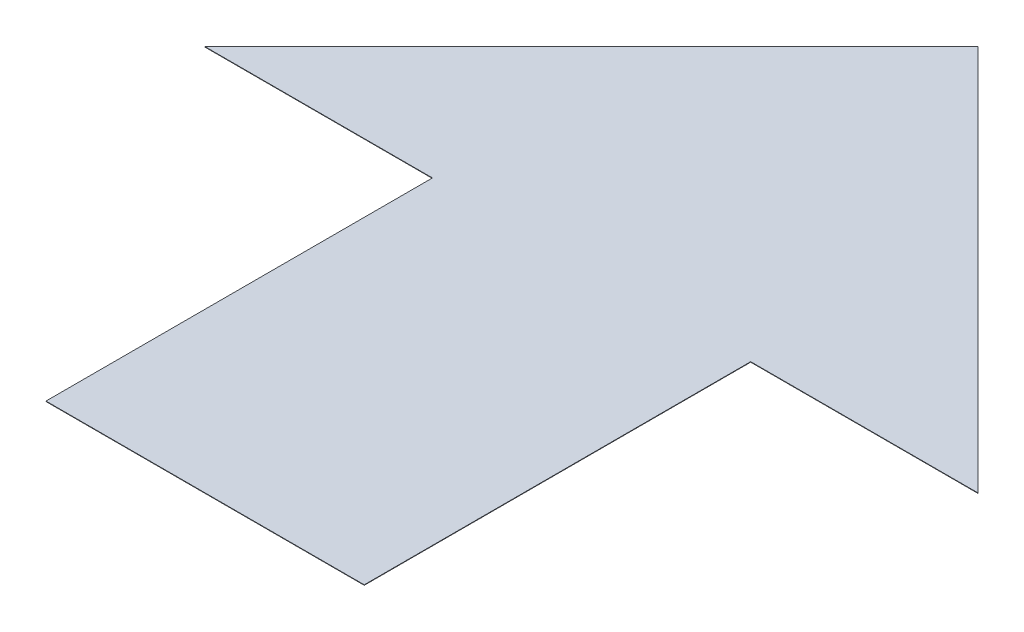
SolidWorks part; units mm, degrees
ref_plane "Front Plane" through (0, 0, 0) normal (0, 0, 1) x (1, 0, 0)
ref_plane "Top Plane" through (0, 0, 0) normal (0, 1, 0) x (1, 0, 0)
ref_plane "Right Plane" through (0, 0, 0) normal (1, 0, 0) x (0, 0, -1)
sketch "Sketch1" plane through (0, 0, 0) normal (0, 1, 0) x (1, 0, 0)
  line L0 (0, 0) -> (0, -50000) construction
  line L1 (-85, -85) -> (85, -85) construction
  line L2 (-85, -85) -> (-85, 85) construction
  line L3 (-85, 85) -> (85, 85) construction
  line L4 (85, -85) -> (85, 85) construction
  line L5 (-85, -85) -> (85, 85) construction
  line L6 (-85, 85) -> (85, -85) construction
  line L7 (35, -85) -> (-35, -85)
  line L8 (-35, -85) -> (-35, 0)
  line L9 (-35, 0) -> (-85, 0)
  line L10 (-85, 0) -> (0, 85)
  line L11 (35, -85) -> (35, 0)
  line L12 (35, 0) -> (85, 0)
  line L13 (85, 0) -> (0, 85)
  point P0 (0, 0)
  point P14 (0, -85)
  dimension "D1" = 170
  dimension "D2" = 45
  dimension "D3" = 35
extrude "Boss-Extrude1" add sketch "Sketch1" along normal mid plane 0.1
